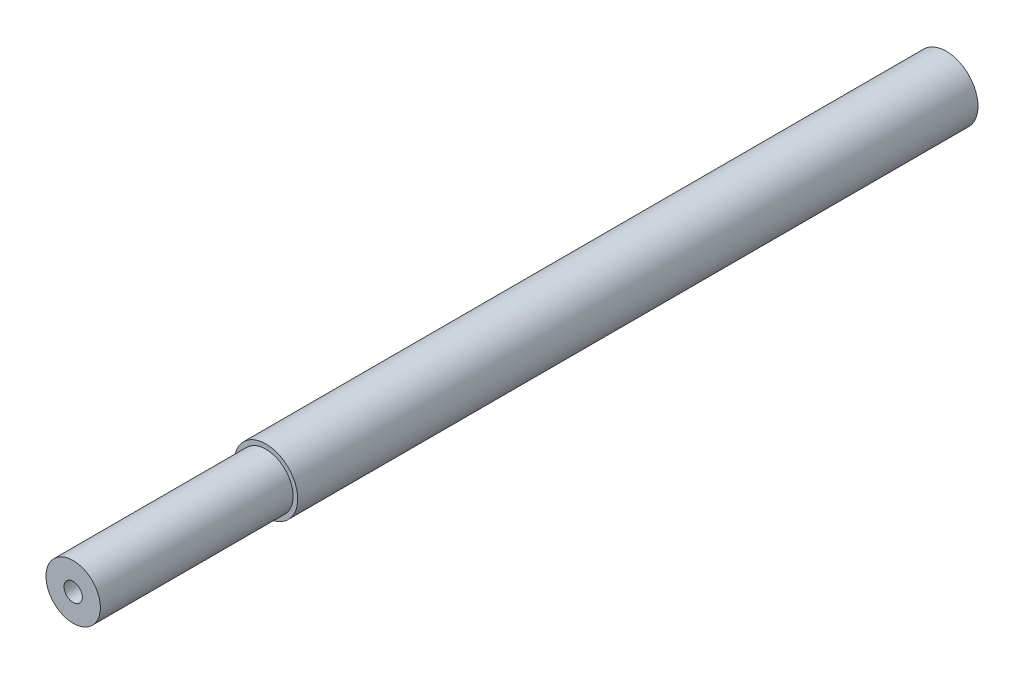
SolidWorks part; units mm, degrees
ref_plane "Front Plane" through (0, 0, 0) normal (0, 0, 1) x (1, 0, 0)
ref_plane "Top Plane" through (0, 0, 0) normal (0, 1, 0) x (1, 0, 0)
ref_plane "Right Plane" through (0, 0, 0) normal (1, 0, 0) x (0, 0, -1)
sketch "Sketch1" plane through (0, 0, 0) normal (1, 0, 0) x (0, 0, -1)
  line L0 (0, 0) -> (146.042, 0) construction
  line L1 (185, 0) -> (185, 7)
  line L3 (-7.5, 6) -> (-7.5, 0)
  line L4 (-7.5, 0) -> (185, 0)
  line L5 (-7.5, 6) -> (35, 6)
  line L6 (35, 6) -> (35, 7)
  line L7 (35, 7) -> (185, 7)
  line L8 (-8, 6) -> (-8, -6) construction
  line L9 (35, -12) -> (35, 12) construction
  line L10 (35, -35.1468) -> (35, 50) construction
  dimension "D1" = 12
  dimension "D2" = 0.5
  dimension "D3" = 14
  dimension "D4" = 150
revolve "Revolve1" add sketch "Sketch1" angle 360 about L0
sketch "Sketch2" plane through (0, 0, 7.5) normal (0, 0, 1) x (1, 0, 0)
  circle A0 centre (0, 0) radius 2.0193
  dimension "D1" = 4.0386
extrude "Cut-Extrude1" cut sketch "Sketch2" against normal blind 25
